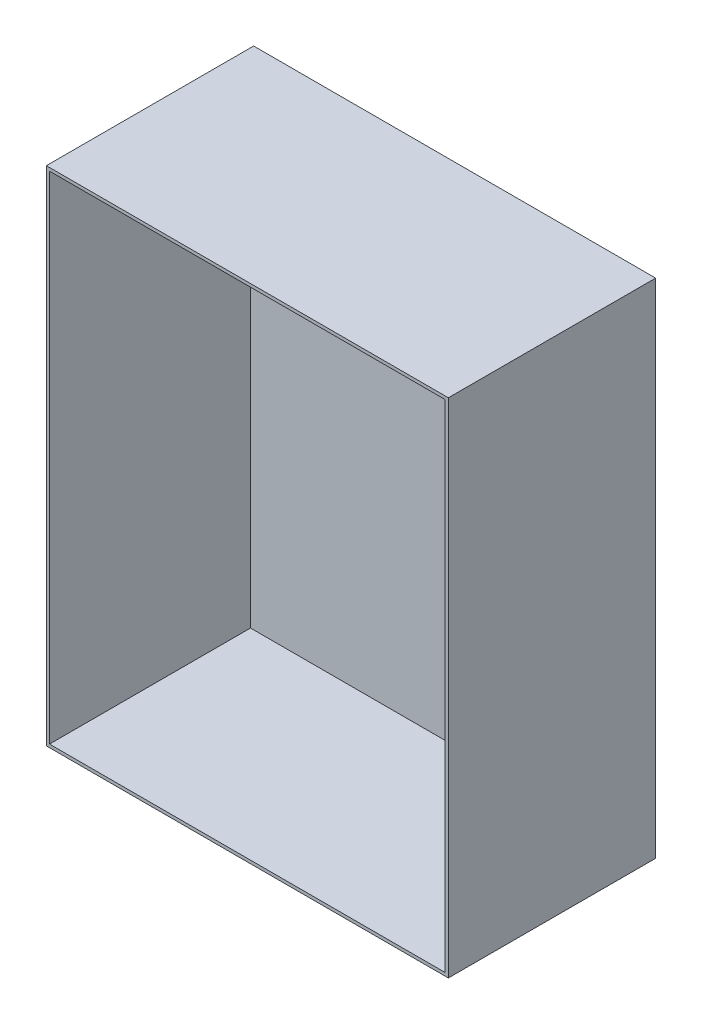
SolidWorks part; units mm, degrees
ref_plane "Front Plane" through (0, 0, 0) normal (0, 0, 1) x (1, 0, 0)
ref_plane "Top Plane" through (0, 0, 0) normal (0, 1, 0) x (1, 0, 0)
ref_plane "Right Plane" through (0, 0, 0) normal (1, 0, 0) x (0, 0, -1)
sketch "Sketch1" plane through (0, 0, 0) normal (0, 0, 1) x (1, 0, 0)
  line L1 (0, 0) -> (-101.6, 0)
  line L2 (0, 0) -> (0, 127)
  line L3 (0, 127) -> (-101.6, 127)
  line L4 (-101.6, 0) -> (-101.6, 127)
  dimension "D1" = 127
  dimension "D2" = 101.6
extrude "Boss-Extrude1" add sketch "Sketch1" along normal blind 1.5875
sketch "Sketch2" plane through (0, 0, 1.5875) normal (0, 0, 1) x (1, 0, 0)
  line L1 (-101.6, 127) -> (0, 127)
  line L2 (-101.6, 127) -> (-101.6, 0)
  line L3 (-101.6, 0) -> (0, 0)
  line L4 (0, 127) -> (0, 0)
extrude "Extrude-Thin1" add sketch "Sketch2" along normal blind 50.8 thin
